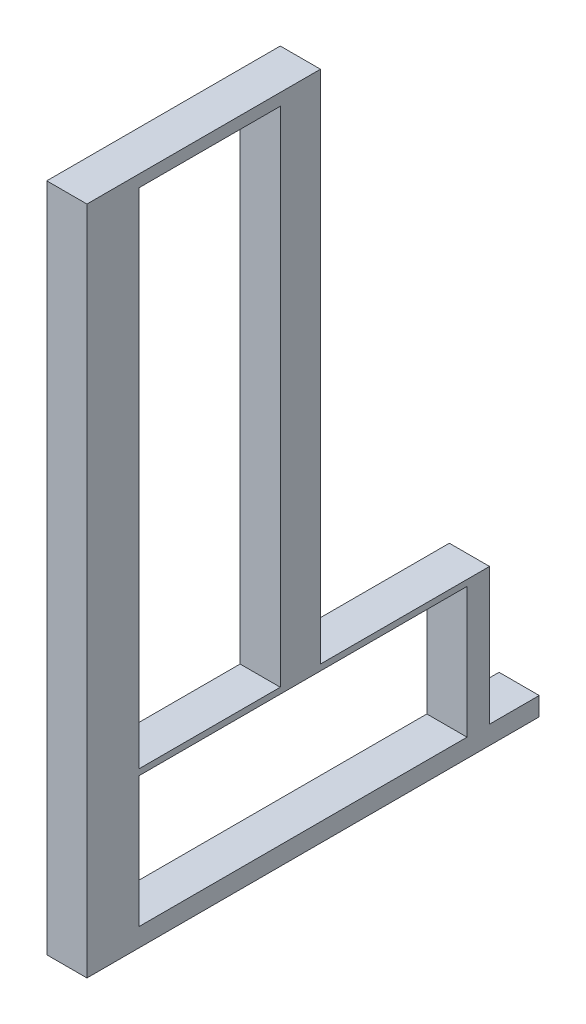
SolidWorks part; units mm, degrees
ref_plane "Front Plane" through (0, 0, 0) normal (0, 0, 1) x (1, 0, 0)
ref_plane "Top Plane" through (0, 0, 0) normal (0, 1, 0) x (1, 0, 0)
ref_plane "Right Plane" through (0, 0, 0) normal (1, 0, 0) x (0, 0, -1)
ref_plane "Plane1" through (-1.651, 0, 0) normal (1, 0, 0) x (0, 0, -1)
sketch "Sketch2" plane through (-1.651, 0, 0) normal (1, 0, 0) x (0, 0, -1)
  line L0 (0, 85) -> (0, -85) construction
  line L1 (4.0259, -78.4236) -> (4.0259, -89.2186) construction
  line L2 (-1.6002, 87.5654) -> (43.1038, 87.5654) construction
  line L3 (-1.6002, 87.5654) -> (-1.6002, -71.4386) construction
  line L4 (-1.6002, -71.4386) -> (43.1038, -71.4386) construction
  line L5 (43.1038, 87.5654) -> (43.1038, -71.4386) construction
  line L6 (6.5659, -91.7586) -> (95.1611, -91.7586) construction
  line L7 (97.7011, -89.2186) -> (97.7011, -88.5836) construction
  line L8 (97.7011, -88.5836) -> (105.1687, -88.5836) construction
  line L9 (105.1687, -88.5836) -> (105.1687, -79.0586) construction
  line L10 (105.1687, -79.0586) -> (97.7011, -79.0586) construction
  line L11 (97.7011, -79.0586) -> (97.7011, -78.4236) construction
  line L12 (95.1611, -75.8836) -> (6.5659, -75.8836) construction
  line L13 (4.0259, -98.7436) -> (4.0259, -109.5386) construction
  line L14 (6.5659, -112.0786) -> (95.1611, -112.0786) construction
  line L15 (97.7011, -109.5386) -> (97.7011, -108.9036) construction
  line L16 (97.7011, -108.9036) -> (105.1687, -108.9036) construction
  line L17 (105.1687, -108.9036) -> (105.1687, -99.3786) construction
  line L18 (105.1687, -99.3786) -> (97.7011, -99.3786) construction
  line L19 (97.7011, -99.3786) -> (97.7011, -98.7436) construction
  line L20 (95.1611, -96.2036) -> (6.5659, -96.2036) construction
  arc A0 (95.1611, -91.7586) -> (97.7011, -89.2186) centre (95.1611, -89.2186) ccw construction
  arc A1 (97.7011, -78.4236) -> (95.1611, -75.8836) centre (95.1611, -78.4236) ccw construction
  arc A2 (4.0259, -89.2186) -> (6.5659, -91.7586) centre (6.5659, -89.2186) ccw construction
  arc A3 (4.0259, -78.4236) -> (6.5659, -75.8836) centre (6.5659, -78.4236) cw construction
  arc A4 (95.1611, -112.0786) -> (97.7011, -109.5386) centre (95.1611, -109.5386) ccw construction
  arc A5 (97.7011, -98.7436) -> (95.1611, -96.2036) centre (95.1611, -98.7436) ccw construction
  arc A6 (4.0259, -109.5386) -> (6.5659, -112.0786) centre (6.5659, -109.5386) ccw construction
  arc A7 (4.0259, -98.7436) -> (6.5659, -96.2036) centre (6.5659, -98.7436) cw construction
  point P2 (0, 0)
  dimension "D6" = 2.54
  dimension "D15" = 2.54
  dimension "D1" = 170
  dimension "D2" = 1.6002
  dimension "D3" = 44.704
  dimension "D4" = 9.525
  dimension "D5" = 88.5952
  dimension "D7" = 15.875
  dimension "D8" = 7.4676
  dimension "D9" = 159.004
  dimension "D10" = 4.445
  dimension "D11" = 4.0259
  dimension "D12" = 2.5654
  dimension "D13" = 9.525
  dimension "D14" = 88.5952
  dimension "D16" = 15.875
  dimension "D17" = 7.4676
  dimension "D18" = 4.445
  dimension "D19" = 40.64
ref_plane "Plane3" through (0, 0, 0) normal (0, 0, 1) x (0, -1, 0)
sketch "Sketch12" plane through (0, 0, 0) normal (0, 0, 1) x (0, -1, 0)
  line L0 (-87.5654, -1.651) -> (71.4386, -1.651) construction
  line L1 (-85, -1.651) -> (85, -1.651) construction
  line L2 (-85, -1.651) -> (-85, -171.651) construction
  line L3 (-85, -171.651) -> (85, -171.651) construction
  line L4 (85, -1.651) -> (85, -171.651) construction
  line L5 (-85, -1.651) -> (85, -1.651) construction
ref_plane "Plane2" through (10.16, 0, 0) normal (1, 0, 0) x (0, 0, -1)
sketch "Sketch3" plane through (10.16, 0, 0) normal (1, 0, 0) x (0, 0, -1)
  line L0 (6.5659, -112.0786) -> (95.1611, -112.0786) construction
  line L1 (115.975, -122.2386) -> (-9.025, -122.2386) construction
  line L2 (115.975, -122.2386) -> (115.975, -185.7386) construction
  line L3 (115.975, -185.7386) -> (-9.025, -185.7386) construction
  line L4 (-9.025, -122.2386) -> (-9.025, -185.7386) construction
  line L5 (-9.025, -128.2386) -> (-3.025, -128.2386) construction
  line L6 (-3.025, -128.2386) -> (-3.025, -122.2386) construction
  line L7 (109.975, -185.7386) -> (109.975, -179.7386) construction
  line L8 (109.975, -179.7386) -> (115.975, -179.7386) construction
  line L9 (0, 85) -> (0, -85) construction
  point P12 (-3.025, -179.7386)
  point P14 (109.975, -128.2386)
  point P15 (109.975, -153.9886)
  point P16 (-3.025, -153.9886)
  point P18 (109.975, -179.7386)
  point P21 (115.975, -153.9886)
  point P23 (-3.025, -128.2386)
  dimension "D1" = 9.025
  dimension "D2" = 63.5
  dimension "D3" = 125
  dimension "D4" = 10.16
  dimension "D5" = 6
sketch "Sketch4" plane through (0, 0, 0) normal (1, 0, 0) x (0, 0, -1)
  line L0 (105.1687, -88.5836) -> (105.1687, -79.0586) construction
  line L1 (55.8038, 91.35) -> (-17.9917, 91.35)
  line L3 (124.9417, -120.4686) -> (-17.9917, -120.4686)
  line L4 (-17.9917, 91.35) -> (-17.9917, -120.4686)
  line L7 (-1.6002, 87.5654) -> (43.1038, 87.5654)
  line L10 (-1.6002, -114.6186) -> (102.1207, -114.6186)
  line L11 (-1.6002, 87.5654) -> (43.1038, 87.5654) construction
  line L13 (-1.6002, -114.6186) -> (-1.6002, -73.3436)
  line L14 (115.975, -122.2386) -> (-9.025, -122.2386) construction
  line L15 (43.1038, 87.5654) -> (43.1038, -71.4386)
  line L16 (43.1038, -71.4386) -> (-1.6002, -71.4386)
  line L17 (-1.6002, -73.3436) -> (102.1207, -73.3436)
  line L18 (124.9417, -114.6186) -> (124.9417, -120.4686)
  line L19 (55.8038, 91.35) -> (55.8038, -71.4386)
  line L20 (55.8038, -71.4386) -> (109.2327, -71.4386)
  line L21 (-1.6002, -71.4386) -> (-1.6002, 87.5654)
  line L24 (6.5659, -112.0786) -> (95.1611, -112.0786) construction
  line L25 (95.1611, -75.8836) -> (6.5659, -75.8836) construction
  line L26 (102.1207, -73.3436) -> (102.1207, -114.6186)
  line L27 (109.2327, -71.4386) -> (109.2327, -114.6186)
  line L29 (109.2327, -114.6186) -> (124.9417, -114.6186)
  line L31 (115.975, -122.2386) -> (115.975, -185.7386) construction
  line L32 (-9.025, -122.2386) -> (-9.025, -185.7386) construction
  dimension "D2" = 2.54
  dimension "D3" = 1.77
  dimension "D5" = 12.7
  dimension "D6" = 2.54
  dimension "D7" = 8.9667
  dimension "D8" = 6.35
  dimension "D9" = 7.112
  dimension "D10" = 4.064
  dimension "D11" = 8.9667
extrude "Boss-Extrude1" add sketch "Sketch4" along normal blind 12.7
sketch "Sketch7" plane through (0, 0, -109.2327) normal (0, 0, -1) x (-1, 0, 0)
  line L0 (0, -114.6186) -> (0, -71.4386) construction
  point P0 (-5.08, -95.6956)
  point P1 (-5.08, -75.3756)
  dimension "D1" = 13.208
  dimension "D2" = 20.32
  dimension "D3" = 5.08
hole_wizard "#18 (0.1695) Diameter Hole1" positions "Sketch7" profile "Sketch8" hole size "#18" standard "ANSI Inch"
sketch "Sketch8" plane through (5.08, -95.6956, -109.2327) normal (1, 0, 0) x (0, 1, 0)
  line L0 (0, 0) -> (0, 5.8654)
  line L1 (0, 5.8654) -> (2.1526, 4.572)
  line L2 (2.1526, 4.572) -> (2.1526, 0.635)
  line L3 (2.1526, 0.635) -> (2.7876, 0)
  line L5 (2.7876, 0) -> (0, 0)
  line L6 (-2.1526, 0.635) -> (-2.7876, 0) construction
  line L10 (0, 5.8654) -> (-2.1527, 4.572) construction
  line L11 (0, -6.35) -> (0, 107.95) construction
  dimension "Hole Dia." = 4.3053
  dimension "Hole Depth" = 4.572
  dimension "Near C'Sink Dia." = 5.5753
  dimension "Near C'Sink Angle" = 90
  dimension "Drill Angle" = 118
sketch "Sketch11" plane through (0, 0, 0) normal (-1, 0, 0) x (0, 0, 1)
  line L0 (1.6002, -114.6186) -> (-102.1207, -114.6186) construction
  line L1 (1.6002, -73.3436) -> (13.7583, -73.3436)
  line L2 (1.6002, -73.3436) -> (1.6002, -114.6186)
  line L3 (1.6002, -114.6186) -> (13.7583, -114.6186)
  line L4 (13.7583, -73.3436) -> (13.7583, -114.6186)
  line L5 (17.9917, 91.35) -> (17.9917, -120.4686) construction
  dimension "D1" = 4.2333
extrude "Cut-Extrude3" cut sketch "Sketch11" against normal blind 1.27
sketch "Sketch9" plane through (0, -120.4686, 0) normal (0, -1, 0) x (1, 0, 0)
  line L0 (3.175, 13.7583) -> (6.35, 16.9333)
  line L1 (3.175, 13.7583) -> (6.35, 10.5833)
  line L2 (6.35, 16.9333) -> (9.525, 13.7583)
  line L3 (6.35, 10.5833) -> (9.525, 13.7583)
  line L4 (3.175, 13.7583) -> (9.525, 13.7583) construction
  line L5 (6.35, 16.9333) -> (6.35, 10.5833) construction
  line L6 (3.175, -120.7083) -> (6.35, -117.5333)
  line L7 (3.175, -120.7083) -> (6.35, -123.8833)
  line L8 (6.35, -117.5333) -> (9.525, -120.7083)
  line L9 (6.35, -123.8833) -> (9.525, -120.7083)
  line L10 (3.175, -120.7083) -> (9.525, -120.7083) construction
  line L11 (6.35, -117.5333) -> (6.35, -123.8833) construction
  line L12 (12.7, 17.9917) -> (12.7, -124.9417) construction
  line L13 (12.7, 17.9917) -> (0, 17.9917) construction
  line L14 (12.7, -124.9417) -> (0, -124.9417) construction
  point P1 (6.35, 13.7583)
  point P2 (6.35, -120.7083)
  dimension "D1" = 6.35
  dimension "D2" = 6.35
  dimension "D3" = 4.2333
  dimension "D4" = 4.2333
extrude "Cut-Extrude1" cut sketch "Sketch9" against normal blind 5.08
sketch "Sketch10" plane through (0, 0, 0) normal (-1, 0, 0) x (0, 0, 1)
  line L0 (13.7583, 90.2917) -> (16.9333, 87.1167)
  line L1 (13.7583, 90.2917) -> (10.5833, 87.1167)
  line L2 (16.9333, 87.1167) -> (13.7583, 83.9417)
  line L3 (10.5833, 87.1167) -> (13.7583, 83.9417)
  line L4 (13.7583, 90.2917) -> (13.7583, 83.9417) construction
  line L5 (16.9333, 87.1167) -> (10.5833, 87.1167) construction
  line L6 (13.7583, -65.0886) -> (16.9333, -68.2636)
  line L7 (13.7583, -65.0886) -> (10.5833, -68.2636)
  line L8 (16.9333, -68.2636) -> (13.7583, -71.4386)
  line L9 (10.5833, -68.2636) -> (13.7583, -71.4386)
  line L10 (13.7583, -65.0886) -> (13.7583, -71.4386) construction
  line L11 (16.9333, -68.2636) -> (10.5833, -68.2636) construction
  line L12 (-55.8038, 91.35) -> (17.9917, 91.35) construction
  line L16 (17.9917, 91.35) -> (17.9917, -120.4686) construction
  point P1 (13.7583, 87.1167)
  point P2 (13.7583, -68.2636)
  dimension "D1" = 6.35
  dimension "D2" = 4.2333
  dimension "D3" = 4.2333
extrude "Cut-Extrude2" cut sketch "Sketch10" against normal blind 5.08
chamfer "Chamfer1" distance 0.635 angle 45 32 edges at (5.08, -66.6761, 15.3458) (5.08, -69.8511, 15.3458) (5.08, -69.8511, 12.1708) (5.08, -66.6761, 12.1708) (5.08, 88.7042, 15.3458) (5.08, 85.5292, 15.3458) (5.08, 85.5292, 12.1708) (5.08, 88.7042, 12.1708) (4.7625, -115.3886, 15.3458) (7.9375, -115.3886, 15.3458) (7.9375, -115.3886, 12.1708) (4.7625, -115.3886, 12.1708) (4.7625, -115.3886, -119.1208) (7.9375, -115.3886, -119.1208) (7.9375, -115.3886, -122.2958) (4.7625, -115.3886, -122.2958) (0, -69.8511, 12.1708) (0, -69.8511, 15.3458) (0, -66.6761, 15.3458) (0, -66.6761, 12.1708) (0, 85.5292, 15.3458) (0, 85.5292, 12.1708) (0, 88.7042, 15.3458) (0, 88.7042, 12.1708) (4.7625, -120.4686, 15.3458) (7.9375, -120.4686, 15.3458) (7.9375, -120.4686, 12.1708) (4.7625, -120.4686, 12.1708) (4.7625, -120.4686, -119.1208) (7.9375, -120.4686, -119.1208) (7.9375, -120.4686, -122.2958) (4.7625, -120.4686, -122.2958)
